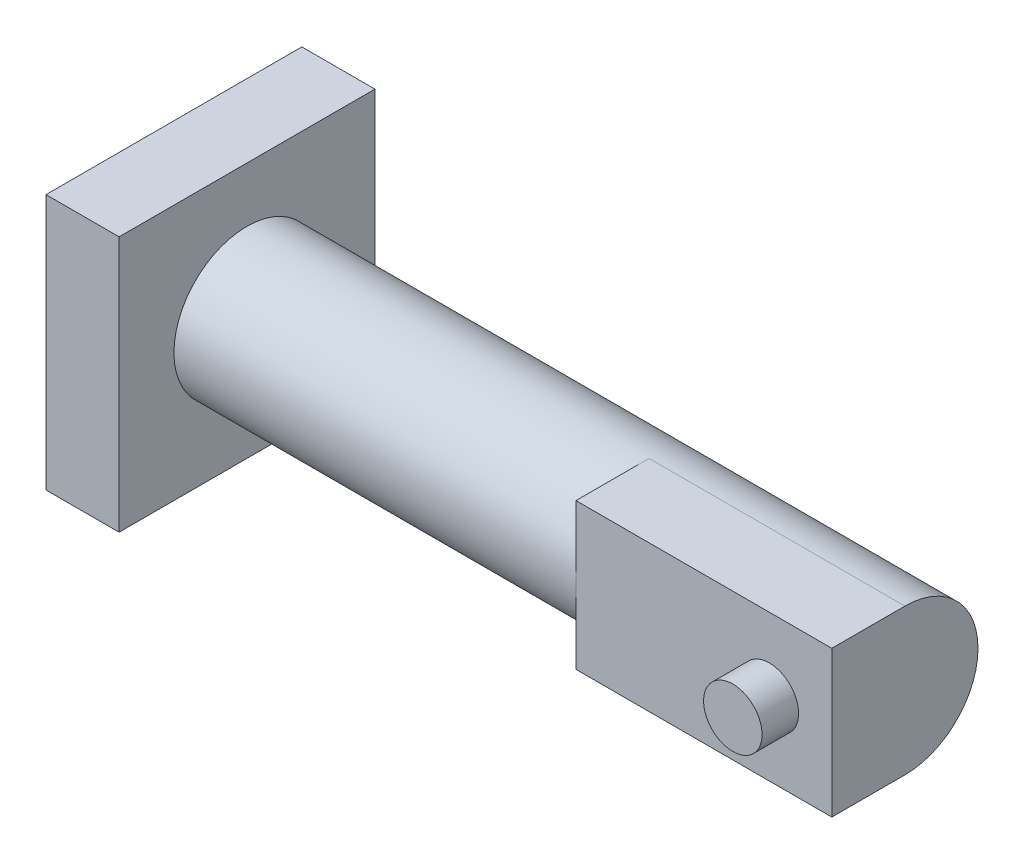
SolidWorks part; units mm, degrees
ref_plane "前视基准面" through (0, 0, 0) normal (0, 0, 1) x (1, 0, 0)
ref_plane "上视基准面" through (0, 0, 0) normal (0, 1, 0) x (1, 0, 0)
ref_plane "右视基准面" through (0, 0, 0) normal (1, 0, 0) x (0, 0, -1)
other "Configuration Table"
sketch "草图1" plane through (0, 0, 0) normal (1, 0, 0) x (0, 0, -1)
  circle A0 centre (0, 0) radius 10
  dimension "D1" = 20
extrude "凸台-拉伸1" add sketch "草图1" along normal blind 90 from offset 0
sketch "草图2" plane through (0, 0, 0) normal (0, 0, 1) x (1, 0, 0)
  line L0 (90, 10) -> (0, 10) construction
  line L1 (90, -10) -> (55, -10)
  line L2 (90, -10) -> (90, 10)
  line L3 (90, 10) -> (55, 10)
  line L4 (55, -10) -> (55, 10)
  dimension "D1" = 35
extrude "凸台-拉伸2" add sketch "草图2" along normal blind 10
sketch "草图3" plane through (0, 0, 10) normal (0, 0, 1) x (1, 0, 0)
  circle A0 centre (81.4586, 0) radius 4
  dimension "D1" = 8
  dimension "D2" = 81.4586
extrude "凸台-拉伸3" add sketch "草图3" along normal blind 5
sketch "草图5" plane through (0, 0, 0) normal (-1, 0, 0) x (0, 0, 1)
  line L1 (-17.5, -17.5) -> (17.5, -17.5)
  line L2 (-17.5, -17.5) -> (-17.5, 17.5)
  line L3 (-17.5, 17.5) -> (17.5, 17.5)
  line L4 (17.5, -17.5) -> (17.5, 17.5)
  line L5 (-17.5, -17.5) -> (17.5, 17.5) construction
  line L6 (-17.5, 17.5) -> (17.5, -17.5) construction
  point P0 (0, 0)
  dimension "D1" = 35
  dimension "D2" = 35
extrude "凸台-拉伸4" add sketch "草图5" along normal blind 10
